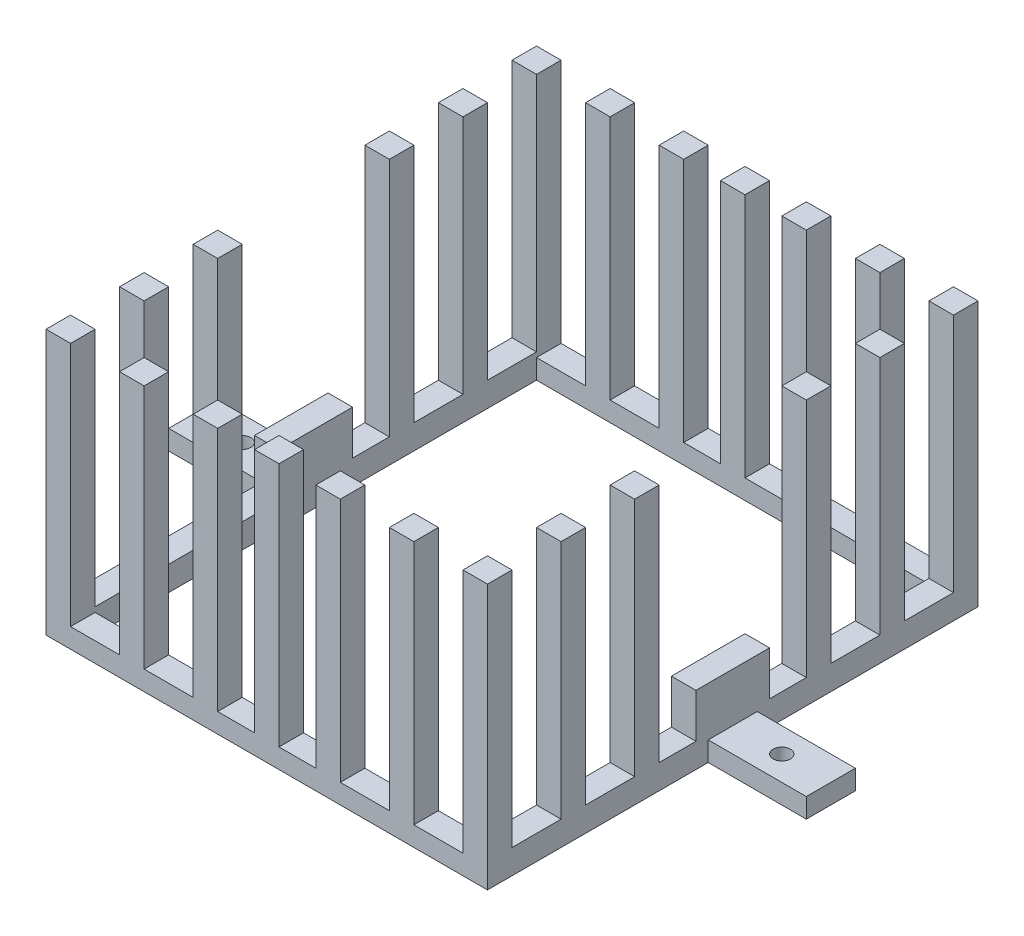
SolidWorks part; units mm, degrees
ref_plane "Front Plane" through (0, 0, 0) normal (0, 0, 1) x (1, 0, 0)
ref_plane "Top Plane" through (0, 0, 0) normal (0, 1, 0) x (1, 0, 0)
ref_plane "Right Plane" through (0, 0, 0) normal (1, 0, 0) x (0, 0, -1)
sketch "Sketch1" plane through (0, 0, 0) normal (0, 1, 0) x (1, 0, 0)
  line L1 (0, 0) -> (90, 0)
  line L2 (0, 0) -> (0, 100)
  line L3 (0, 100) -> (90, 100)
  line L4 (90, 0) -> (90, 100)
  line L5 (-20, 55) -> (-20, 45)
  line L6 (-20, 45) -> (0, 45)
  line L7 (-20, 55) -> (0, 55)
  line L8 (45, 0) -> (45, 100)
  line L9 (110, 45) -> (90, 45)
  line L10 (110, 55) -> (110, 45)
  line L11 (110, 55) -> (90, 55)
  line L12 (5, 95) -> (85, 95)
  line L13 (5, 95) -> (5, 5)
  line L14 (5, 5) -> (85, 5)
  line L15 (85, 95) -> (85, 5)
  circle A0 centre (-10, 50) radius 1.75
  circle A1 centre (100, 50) radius 1.75
  dimension "D3" = 3.5
  dimension "D4" = 10
  dimension "D1" = 90
  dimension "D2" = 100
  dimension "D5" = 5
  dimension "D6" = 5
  dimension "D7" = 5
  dimension "D8" = 5
  dimension "D9" = 45
  dimension "D10" = 45
extrude "Boss-Extrude1" add sketch "Sketch1" along normal blind 4 contours L1 L8 L3 L2 | L8 L1 L4 L3 | L10 L11 L4 L9 A1 | L7 L5 L6 L2 A0
sketch "Sketch2" plane through (0, 4, 0) normal (0, 1, 0) x (1, 0, 0)
  line L1 (0, 0) -> (90, 0)
  line L2 (0, 0) -> (0, 100)
  line L3 (0, 100) -> (90, 100)
  line L4 (90, 0) -> (90, 100)
  line L5 (5, 95) -> (85, 95)
  line L6 (5, 95) -> (5, 5)
  line L7 (5, 5) -> (85, 5)
  line L8 (85, 95) -> (85, 5)
  line M9 (90, 55) -> (90, 100)
  line M10 (90, 100) -> (0, 100)
  line M11 (0, 100) -> (0, 55)
  line M15 (0, 45) -> (0, 0)
  line M16 (0, 0) -> (90, 0)
  line M17 (90, 0) -> (90, 45)
  line M21 (85, 5) -> (5, 5)
  line M22 (5, 5) -> (5, 95)
  line M23 (5, 95) -> (85, 95)
  line M24 (85, 95) -> (85, 5)
extrude "Boss-Extrude2" add sketch "Sketch2" along normal blind 50 contours L4 L2 M17 M9 M10 M11 M15 M16 M24 M21 M22 M23
sketch "Sketch3" plane through (0, 54, 0) normal (0, 1, 0) x (1, 0, 0)
  line L0 (90, 0) -> (90, 100) construction
  line L1 (90, 42.5) -> (85, 42.5)
  line L2 (90, 42.5) -> (90, 57.5)
  line L3 (90, 57.5) -> (85, 57.5)
  line L4 (85, 42.5) -> (85, 57.5)
  line L5 (85, 95) -> (85, 5) construction
  line L6 (0, 50) -> (90, 50)
  line L7 (0, 100) -> (0, 0) construction
  line L8 (45, 100) -> (45, 0)
  line L9 (90, 100) -> (0, 100) construction
  line L10 (0, 0) -> (90, 0) construction
  line L11 (0, 57.5) -> (5, 57.5)
  line L12 (5, 42.5) -> (5, 57.5)
  line L13 (0, 42.5) -> (5, 42.5)
  line L14 (0, 42.5) -> (0, 57.5)
  dimension "D1" = 15
  dimension "D2" = 7.5
extrude "Cut-Extrude1" cut sketch "Sketch3" against normal blind 40 contours L4 L3 L2 L1 | L14 L11 L12 L13
sketch "Sketch4" plane through (0, 0, 0) normal (0, 0, 1) x (1, 0, 0)
  line L0 (5, 49.5) -> (5, 4.5)
  line L1 (5, 4.5) -> (40, 26.2445)
  line L2 (40, 26.2445) -> (5, 49.5)
  line L3 (0, 54) -> (90, 54) construction
  line L4 (0, 0) -> (90, 0) construction
  line L5 (0, 54) -> (0, 0) construction
  line L6 (45, 0) -> (45, 54)
  line L7 (85, 4.5) -> (50, 26.2445)
  line L8 (85, 49.5) -> (85, 4.5)
  line L9 (50, 26.2445) -> (85, 49.5)
  line L10 (0, 27) -> (90, 27)
  line L11 (90, 54) -> (90, 0) construction
  line L12 (10, 4.5) -> (80, 4.5)
  line L13 (10, 4.5) -> (45, 22)
  line L14 (45, 22) -> (80, 4.5)
  line L15 (10, 49.5) -> (45, 32)
  line L16 (10, 49.5) -> (80, 49.5)
  line L17 (45, 32) -> (80, 49.5)
  dimension "D1" = 45
  dimension "D2" = 4.5
  dimension "D3" = 4.5
  dimension "D4" = 5
  dimension "D5" = 5
  dimension "D6" = 5
  dimension "D7" = 5
  dimension "D8" = 5
extrude "Cut-Extrude2" [suppressed] cut sketch "Sketch4" against normal through all contours L9 L7 L8 | L10 L0 L1 L2 | L0 L10 L2 | L16 L15 L6 | L6 L17 L16 | L9 L10 L8 | L14 L6 L12 | L13 L12 L6
sketch "Sketch5" plane through (0, 0, 0) normal (-1, 0, 0) x (0, 0, 1)
  line L0 (-100, 54) -> (-57.5, 54) construction
  line L1 (-95, 49) -> (-81.25, 49)
  line L2 (-95, 49) -> (-95, 5)
  line L3 (-95, 5) -> (-81.25, 5)
  line L4 (-62.5, 49) -> (-62.5, 5)
  line L5 (-55, 0) -> (-100, 0) construction
  line L6 (-57.5, 14) -> (-57.5, 54) construction
  line L7 (-100, 54) -> (-100, 0) construction
  line L8 (-76.25, 49) -> (-76.25, 5)
  line L9 (-81.25, 49) -> (-81.25, 5)
  line L10 (-50, 14) -> (-50, 4)
  line L11 (-42.5, 14) -> (-57.5, 14) construction
  line L12 (-55, 4) -> (-45, 4) construction
  line L13 (-76.25, 49) -> (-62.5, 49)
  line L14 (-76.25, 5) -> (-62.5, 5)
  line L15 (-23.75, 49) -> (-37.5, 49)
  line L16 (-23.75, 49) -> (-23.75, 5)
  line L17 (-23.75, 5) -> (-37.5, 5)
  line L18 (-37.5, 49) -> (-37.5, 5)
  line L19 (-5, 49) -> (-18.75, 49)
  line L20 (-18.75, 49) -> (-18.75, 5)
  line L21 (-5, 5) -> (-18.75, 5)
  line L22 (-5, 49) -> (-5, 5)
  dimension "D1" = 5
  dimension "D2" = 5
  dimension "D3" = 5
  dimension "D4" = 5
  dimension "D5" = 5
  dimension "D6" = 13.75
  dimension "D7" = 13.75
extrude "Cut-Extrude3" [suppressed] cut sketch "Sketch5" against normal through all contours L9 L1 L2 L3 | L8 L14 L4 L13 | L15 L18 L17 L16 | L22 L19 L20 L21
sketch "Sketch6" plane through (0, 0, -100) normal (0, 0, -1) x (-1, 0, 0)
  line L0 (-90, 54) -> (0, 54) construction
  line L1 (-85, 54) -> (-75, 54)
  line L2 (-85, 54) -> (-85, 4)
  line L3 (-85, 4) -> (-75, 4)
  line L4 (-75, 54) -> (-75, 4)
  line L5 (0, 0) -> (-90, 0) construction
  line L6 (-90, 54) -> (-90, 0) construction
  line L7 (-45, 54) -> (-45, 0)
  line L8 (-35, 4) -> (-42.5, 4)
  line L9 (-70, 54) -> (-60, 54)
  line L10 (-70, 54) -> (-70, 4)
  line L11 (-70, 4) -> (-60, 4)
  line L12 (-60, 54) -> (-60, 4)
  line L13 (-55, 54) -> (-47.5, 54)
  line L14 (-55, 54) -> (-55, 4)
  line L15 (-55, 4) -> (-47.5, 4)
  line L16 (-47.5, 54) -> (-47.5, 4)
  line L17 (-42.5, 54) -> (-42.5, 4)
  line L18 (-35, 54) -> (-42.5, 54)
  line L19 (-35, 54) -> (-35, 4)
  line L20 (-20, 4) -> (-30, 4)
  line L21 (-30, 54) -> (-30, 4)
  line L22 (-20, 54) -> (-30, 54)
  line L23 (-20, 54) -> (-20, 4)
  line L24 (-5, 4) -> (-15, 4)
  line L25 (-15, 54) -> (-15, 4)
  line L26 (-5, 54) -> (-15, 54)
  line L27 (-5, 54) -> (-5, 4)
  line M16 (0, 54) -> (-90, 54)
  dimension "D1" = 4
  dimension "D2" = 5
  dimension "D3" = 10
  dimension "D4" = 10
  dimension "D5" = 5
  dimension "D6" = 5
  dimension "D7" = 2.5
extrude "Cut-Extrude5" cut sketch "Sketch6" against normal through all contours L4 L2 L3 M16 | L12 L10 L11 M16 | L16 L14 L15 M16 | L19 L17 L8 M16 | L23 L21 L20 M16 | L27 L25 L24 M16
sketch "Sketch8" plane through (90, 0, 0) normal (1, 0, 0) x (0, 0, -1)
  line L0 (0, 54) -> (42.5, 54) construction
  line L1 (5, 54) -> (15, 54)
  line L2 (5, 54) -> (5, 5)
  line L3 (5, 5) -> (15, 5)
  line L4 (15, 54) -> (15, 5)
  line L5 (0, 54) -> (0, 0) construction
  line L6 (0, 0) -> (45, 0) construction
  line L7 (50, 14) -> (50, 4)
  line L8 (20, 54) -> (30, 54)
  line L9 (20, 54) -> (20, 5)
  line L10 (20, 5) -> (30, 5)
  line L11 (30, 54) -> (30, 5)
  line L12 (42.5, 54) -> (35, 54)
  line L13 (42.5, 54) -> (42.5, 5)
  line L14 (42.5, 5) -> (35, 5)
  line L15 (35, 54) -> (35, 5)
  line L16 (42.5, 14) -> (57.5, 14) construction
  line L17 (45, 4) -> (55, 4) construction
  line L18 (57.5, 5) -> (65, 5)
  line L19 (65, 54) -> (65, 5)
  line L20 (57.5, 54) -> (65, 54)
  line L21 (57.5, 54) -> (57.5, 5)
  line L22 (80, 5) -> (70, 5)
  line L23 (70, 54) -> (70, 5)
  line L24 (80, 54) -> (70, 54)
  line L25 (80, 54) -> (80, 5)
  line L26 (95, 5) -> (85, 5)
  line L27 (85, 54) -> (85, 5)
  line L28 (95, 54) -> (85, 54)
  line L29 (95, 54) -> (95, 5)
  line M14 (42.5, 14) -> (42.5, 54)
  line M15 (42.5, 54) -> (0, 54)
  line M23 (100, 54) -> (57.5, 54)
  line M24 (57.5, 54) -> (57.5, 14)
  dimension "D1" = 5
  dimension "D2" = 5
  dimension "D3" = 10
  dimension "D4" = 5
  dimension "D5" = 10
  dimension "D6" = 5
extrude "Cut-Extrude6" cut sketch "Sketch8" against normal through all contours L4 L2 L3 M15 | L11 L9 L10 M15 | L15 L14 L13 M15 M14 | L21 L18 L19 M24 M23 | L25 L23 L22 M23 | L29 L27 L26 M23
